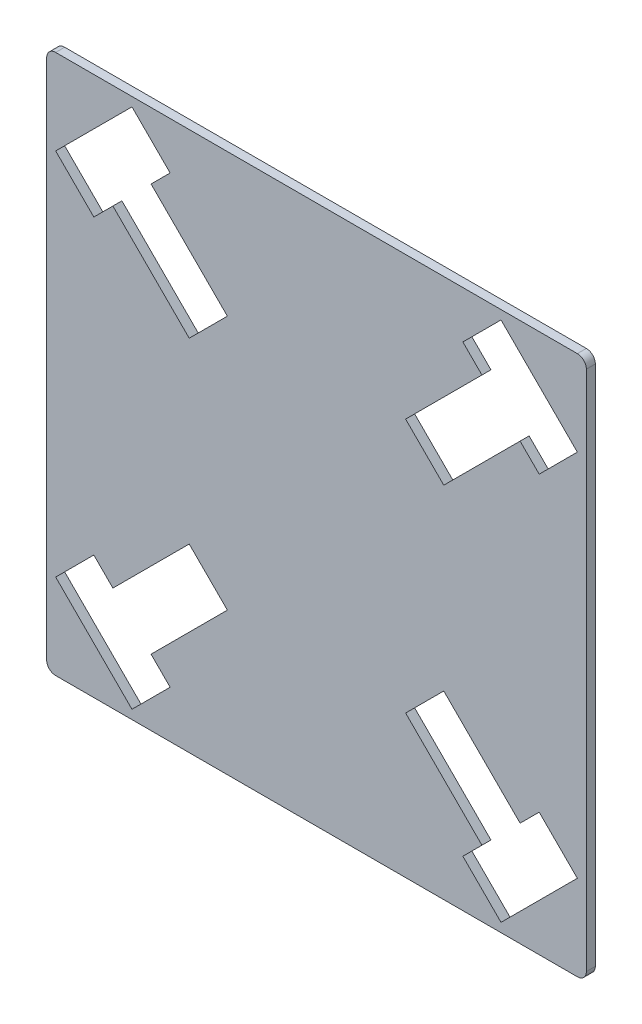
SolidWorks part; units mm, degrees
ref_plane "Plan de face" through (0, 0, 0) normal (0, 0, 1) x (1, 0, 0)
ref_plane "Plan de dessus" through (0, 0, 0) normal (0, 1, 0) x (1, 0, 0)
ref_plane "Plan de droite" through (0, 0, 0) normal (1, 0, 0) x (0, 0, -1)
sketch "Esquisse1" plane through (0, 0, 0) normal (0, 0, 1) x (1, 0, 0)
  line L0 (150, 150) -> (-150, -150) construction
  line L1 (-150, 150) -> (150, 150)
  line L2 (-150, 150) -> (-150, -150)
  line L3 (-150, -150) -> (150, -150)
  line L4 (150, 150) -> (150, -150)
  line L5 (-150, 150) -> (150, -150) construction
  point P4 (0, 0)
  dimension "D1" = 300
  dimension "D2" = 300
extrude "Boss.-Extru.1" add sketch "Esquisse1" along normal blind 5
sketch "Esquisse2" plane through (0, 0, 0) normal (0, 0, 1) x (1, 0, 0)
  line L0 (-150, 150) -> (150, -150) construction
  line L1 (-150, -150) -> (150, 150) construction
  line L2 (-70.7538, 49.5406) -> (-49.5406, 70.7538)
  line L3 (-49.5406, 70.7538) -> (-91.967, 113.1802)
  line L4 (-91.967, 113.1802) -> (-81.3604, 123.7868)
  line L5 (-81.3604, 123.7868) -> (-102.5736, 145)
  line L6 (-102.5736, 145) -> (-145, 102.5736)
  line L7 (-145, 102.5736) -> (-123.7868, 81.3604)
  line L8 (-123.7868, 81.3604) -> (-113.1802, 91.967)
  line L9 (-113.1802, 91.967) -> (-70.7538, 49.5406)
  line L10 (-150, 150) -> (-150, -150) construction
  line L11 (150, 150) -> (-150, 150) construction
  line L12 (0, 150) -> (0, -150) construction
  line L13 (-150, -150) -> (150, -150) construction
  line L14 (-150, 0) -> (150, 0) construction
  line L15 (150, -150) -> (150, 150) construction
  line L16 (145, 102.5736) -> (123.7868, 81.3604)
  line L17 (102.5736, 145) -> (145, 102.5736)
  line L18 (81.3604, 123.7868) -> (102.5736, 145)
  line L19 (70.7538, 49.5406) -> (49.5406, 70.7538)
  line L20 (49.5406, 70.7538) -> (91.967, 113.1802)
  line L21 (113.1802, 91.967) -> (70.7538, 49.5406)
  line L22 (123.7868, 81.3604) -> (113.1802, 91.967)
  line L23 (91.967, 113.1802) -> (81.3604, 123.7868)
  line L24 (-70.7538, -49.5406) -> (-49.5406, -70.7538)
  line L25 (-113.1802, -91.967) -> (-70.7538, -49.5406)
  line L26 (-49.5406, -70.7538) -> (-91.967, -113.1802)
  line L27 (-91.967, -113.1802) -> (-81.3604, -123.7868)
  line L28 (-123.7868, -81.3604) -> (-113.1802, -91.967)
  line L29 (-145, -102.5736) -> (-123.7868, -81.3604)
  line L30 (-81.3604, -123.7868) -> (-102.5736, -145)
  line L31 (-102.5736, -145) -> (-145, -102.5736)
  line L32 (91.967, -113.1802) -> (81.3604, -123.7868)
  line L33 (81.3604, -123.7868) -> (102.5736, -145)
  line L34 (102.5736, -145) -> (145, -102.5736)
  line L35 (145, -102.5736) -> (123.7868, -81.3604)
  line L36 (123.7868, -81.3604) -> (113.1802, -91.967)
  line L37 (113.1802, -91.967) -> (70.7538, -49.5406)
  line L38 (70.7538, -49.5406) -> (49.5406, -70.7538)
  line L39 (49.5406, -70.7538) -> (91.967, -113.1802)
  point P18 (-60.1472, 60.1472)
  dimension "D1" = 30
  dimension "D2" = 60
  dimension "D3" = 30
  dimension "D4" = 60
  dimension "D5" = 5
  dimension "D6" = 5
extrude "Enlèv. mat.-Extru.1" cut sketch "Esquisse2" along normal blind 5
fillet "Congé1" radius 5 4 edges at (-150, -150, 2.5) (150, -150, 2.5) (150, 150, 2.5) (-150, 150, 2.5)
